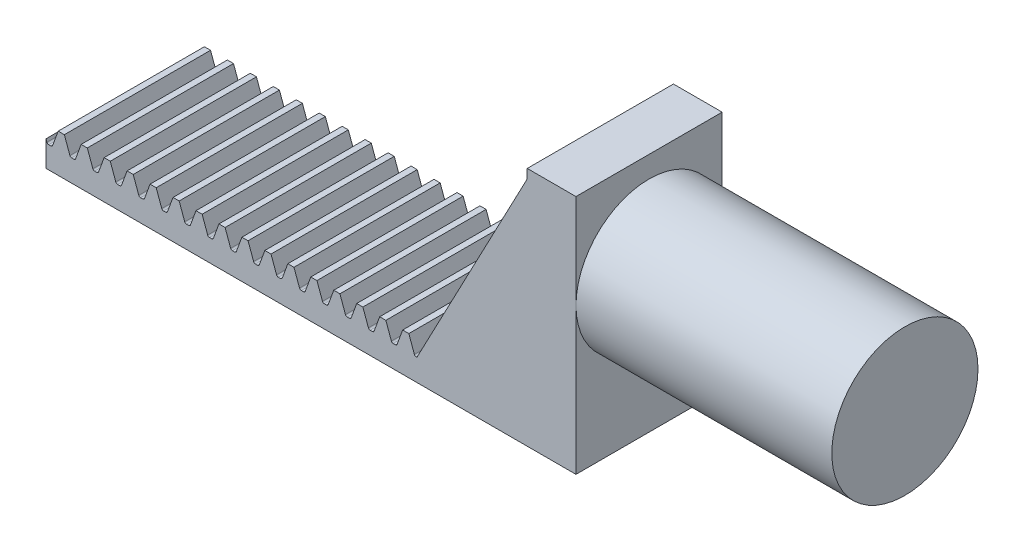
SolidWorks part; units mm, degrees
ref_plane "Front Plane" through (0, 0, 0) normal (0, 0, 1) x (1, 0, 0)
ref_plane "Top Plane" through (0, 0, 0) normal (0, 1, 0) x (1, 0, 0)
ref_plane "Right Plane" through (0, 0, 0) normal (1, 0, 0) x (0, 0, -1)
ref_plane "Plane1" through (0, 0, 19) normal (0, 0, 1) x (1, 0, 0)
sketch "Sketch1" plane through (0, 0, 19) normal (0, 0, 1) x (1, 0, 0)
  line L0 (0, -23.5) -> (0, -29.5)
  line L1 (0, -29.5) -> (131.9469, -29.5)
  line L2 (131.9469, -29.5) -> (131.9469, -23.5)
  line L3 (131.9469, -23.5) -> (131.6361, -23.5)
  line L4 (131.1663, -23.171) -> (129.6482, -19)
  line L5 (129.6482, -19) -> (127.9624, -19)
  line L6 (127.9624, -19) -> (126.4443, -23.171)
  line L7 (125.9745, -23.5) -> (125.3529, -23.5)
  line L8 (124.8831, -23.171) -> (123.365, -19)
  line L9 (123.365, -19) -> (121.6793, -19)
  line L10 (121.6793, -19) -> (120.1611, -23.171)
  line L11 (119.6913, -23.5) -> (119.0698, -23.5)
  line L12 (118.5999, -23.171) -> (117.0818, -19)
  line L13 (117.0818, -19) -> (115.3961, -19)
  line L14 (115.3961, -19) -> (113.8779, -23.171)
  line L15 (113.4081, -23.5) -> (112.7866, -23.5)
  line L16 (112.3167, -23.171) -> (110.7986, -19)
  line L17 (110.7986, -19) -> (109.1129, -19)
  line L18 (109.1129, -19) -> (107.5948, -23.171)
  line L19 (107.1249, -23.5) -> (106.5034, -23.5)
  line L20 (106.0335, -23.171) -> (104.5154, -19)
  line L21 (104.5154, -19) -> (102.8297, -19)
  line L22 (102.8297, -19) -> (101.3116, -23.171)
  line L23 (100.8417, -23.5) -> (100.2202, -23.5)
  line L24 (99.7504, -23.171) -> (98.2322, -19)
  line L25 (98.2322, -19) -> (96.5465, -19)
  line L26 (96.5465, -19) -> (95.0284, -23.171)
  line L27 (94.5585, -23.5) -> (93.937, -23.5)
  line L28 (93.4672, -23.171) -> (91.949, -19)
  line L29 (91.949, -19) -> (90.2633, -19)
  line L30 (90.2633, -19) -> (88.7452, -23.171)
  line L31 (88.2754, -23.5) -> (87.6538, -23.5)
  line L32 (87.184, -23.171) -> (85.6659, -19)
  line L33 (85.6659, -19) -> (83.9801, -19)
  line L34 (83.9801, -19) -> (82.462, -23.171)
  line L35 (81.9922, -23.5) -> (81.3706, -23.5)
  line L36 (80.9008, -23.171) -> (79.3827, -19)
  line L37 (79.3827, -19) -> (77.697, -19)
  line L38 (77.697, -19) -> (76.1788, -23.171)
  line L39 (75.709, -23.5) -> (75.0875, -23.5)
  line L40 (74.6176, -23.171) -> (73.0995, -19)
  line L41 (73.0995, -19) -> (71.4138, -19)
  line L42 (71.4138, -19) -> (69.8957, -23.171)
  line L43 (69.4258, -23.5) -> (68.8043, -23.5)
  line L44 (68.3344, -23.171) -> (66.8163, -19)
  line L45 (66.8163, -19) -> (65.1306, -19)
  line L46 (65.1306, -19) -> (63.6125, -23.171)
  line L47 (63.1426, -23.5) -> (62.5211, -23.5)
  line L48 (62.0512, -23.171) -> (60.5331, -19)
  line L49 (60.5331, -19) -> (58.8474, -19)
  line L50 (58.8474, -19) -> (57.3293, -23.171)
  line L51 (56.8594, -23.5) -> (56.2379, -23.5)
  line L52 (55.7681, -23.171) -> (54.2499, -19)
  line L53 (54.2499, -19) -> (52.5642, -19)
  line L54 (52.5642, -19) -> (51.0461, -23.171)
  line L55 (50.5762, -23.5) -> (49.9547, -23.5)
  line L56 (49.4849, -23.171) -> (47.9667, -19)
  line L57 (47.9667, -19) -> (46.281, -19)
  line L58 (46.281, -19) -> (44.7629, -23.171)
  line L59 (44.2931, -23.5) -> (43.6715, -23.5)
  line L60 (43.2017, -23.171) -> (41.6836, -19)
  line L61 (41.6836, -19) -> (39.9978, -19)
  line L62 (39.9978, -19) -> (38.4797, -23.171)
  line L63 (38.0099, -23.5) -> (37.3883, -23.5)
  line L64 (36.9185, -23.171) -> (35.4004, -19)
  line L65 (35.4004, -19) -> (33.7147, -19)
  line L66 (33.7147, -19) -> (32.1965, -23.171)
  line L67 (31.7267, -23.5) -> (31.1052, -23.5)
  line L68 (30.6353, -23.171) -> (29.1172, -19)
  line L69 (29.1172, -19) -> (27.4315, -19)
  line L70 (27.4315, -19) -> (25.9134, -23.171)
  line L71 (25.4435, -23.5) -> (24.822, -23.5)
  line L72 (24.3521, -23.171) -> (22.834, -19)
  line L73 (22.834, -19) -> (21.1483, -19)
  line L74 (21.1483, -19) -> (19.6302, -23.171)
  line L75 (19.1603, -23.5) -> (18.5388, -23.5)
  line L76 (18.0689, -23.171) -> (16.5508, -19)
  line L77 (16.5508, -19) -> (14.8651, -19)
  line L78 (14.8651, -19) -> (13.347, -23.171)
  line L79 (12.8771, -23.5) -> (12.2556, -23.5)
  line L80 (11.7858, -23.171) -> (10.2676, -19)
  line L81 (10.2676, -19) -> (8.5819, -19)
  line L82 (8.5819, -19) -> (7.0638, -23.171)
  line L83 (6.594, -23.5) -> (5.9724, -23.5)
  line L84 (5.5026, -23.171) -> (3.9844, -19)
  line L85 (3.9844, -19) -> (2.2987, -19)
  line L86 (2.2987, -19) -> (0.7806, -23.171)
  line L87 (0.3108, -23.5) -> (0, -23.5)
  arc A0 (131.6361, -23.5) -> (131.1663, -23.171) centre (131.6361, -23) cw
  arc A1 (126.4443, -23.171) -> (125.9745, -23.5) centre (125.9745, -23) cw
  arc A2 (125.3529, -23.5) -> (124.8831, -23.171) centre (125.3529, -23) cw
  arc A3 (120.1611, -23.171) -> (119.6913, -23.5) centre (119.6913, -23) cw
  arc A4 (119.0698, -23.5) -> (118.5999, -23.171) centre (119.0698, -23) cw
  arc A5 (113.8779, -23.171) -> (113.4081, -23.5) centre (113.4081, -23) cw
  arc A6 (112.7866, -23.5) -> (112.3167, -23.171) centre (112.7866, -23) cw
  arc A7 (107.5948, -23.171) -> (107.1249, -23.5) centre (107.1249, -23) cw
  arc A8 (106.5034, -23.5) -> (106.0335, -23.171) centre (106.5034, -23) cw
  arc A9 (101.3116, -23.171) -> (100.8417, -23.5) centre (100.8417, -23) cw
  arc A10 (100.2202, -23.5) -> (99.7504, -23.171) centre (100.2202, -23) cw
  arc A11 (95.0284, -23.171) -> (94.5585, -23.5) centre (94.5585, -23) cw
  arc A12 (93.937, -23.5) -> (93.4672, -23.171) centre (93.937, -23) cw
  arc A13 (88.7452, -23.171) -> (88.2754, -23.5) centre (88.2754, -23) cw
  arc A14 (87.6538, -23.5) -> (87.184, -23.171) centre (87.6538, -23) cw
  arc A15 (82.462, -23.171) -> (81.9922, -23.5) centre (81.9922, -23) cw
  arc A16 (81.3706, -23.5) -> (80.9008, -23.171) centre (81.3706, -23) cw
  arc A17 (76.1788, -23.171) -> (75.709, -23.5) centre (75.709, -23) cw
  arc A18 (75.0875, -23.5) -> (74.6176, -23.171) centre (75.0875, -23) cw
  arc A19 (69.8957, -23.171) -> (69.4258, -23.5) centre (69.4258, -23) cw
  arc A20 (68.8043, -23.5) -> (68.3344, -23.171) centre (68.8043, -23) cw
  arc A21 (63.6125, -23.171) -> (63.1426, -23.5) centre (63.1426, -23) cw
  arc A22 (62.5211, -23.5) -> (62.0512, -23.171) centre (62.5211, -23) cw
  arc A23 (57.3293, -23.171) -> (56.8594, -23.5) centre (56.8594, -23) cw
  arc A24 (56.2379, -23.5) -> (55.7681, -23.171) centre (56.2379, -23) cw
  arc A25 (51.0461, -23.171) -> (50.5762, -23.5) centre (50.5762, -23) cw
  arc A26 (49.9547, -23.5) -> (49.4849, -23.171) centre (49.9547, -23) cw
  arc A27 (44.7629, -23.171) -> (44.2931, -23.5) centre (44.2931, -23) cw
  arc A28 (43.6715, -23.5) -> (43.2017, -23.171) centre (43.6715, -23) cw
  arc A29 (38.4797, -23.171) -> (38.0099, -23.5) centre (38.0099, -23) cw
  arc A30 (37.3883, -23.5) -> (36.9185, -23.171) centre (37.3883, -23) cw
  arc A31 (32.1965, -23.171) -> (31.7267, -23.5) centre (31.7267, -23) cw
  arc A32 (31.1052, -23.5) -> (30.6353, -23.171) centre (31.1052, -23) cw
  arc A33 (25.9134, -23.171) -> (25.4435, -23.5) centre (25.4435, -23) cw
  arc A34 (24.822, -23.5) -> (24.3521, -23.171) centre (24.822, -23) cw
  arc A35 (19.6302, -23.171) -> (19.1603, -23.5) centre (19.1603, -23) cw
  arc A36 (18.5388, -23.5) -> (18.0689, -23.171) centre (18.5388, -23) cw
  arc A37 (13.347, -23.171) -> (12.8771, -23.5) centre (12.8771, -23) cw
  arc A38 (12.2556, -23.5) -> (11.7858, -23.171) centre (12.2556, -23) cw
  arc A39 (7.0638, -23.171) -> (6.594, -23.5) centre (6.594, -23) cw
  arc A40 (5.9724, -23.5) -> (5.5026, -23.171) centre (5.9724, -23) cw
  arc A41 (0.7806, -23.171) -> (0.3108, -23.5) centre (0.3108, -23) cw
  point P172 (0, 0)
  point P174 (0, 0)
extrude "Boss-Extrude1" add sketch "Sketch1" against normal mid plane 40 from offset 0
scale "Scale1" scale about centroid uniform scaling yes scale factor 0.3
sketch "Sketch8" plane through (0, 0, 25) normal (0, 0, 1) x (1, 0, 0)
  line L0 (82.9123, -26.4286) -> (92.9123, -26.4286)
  line L2 (92.9123, -26.4286) -> (92.9123, -7.4286)
  line L3 (92.9123, -7.4286) -> (82.9123, -26.4286)
  line L4 (46.1814, -26.4286) -> (85.7655, -26.4286) construction
  point P4 (0, 0)
  dimension "D1" = 10
  dimension "D2" = 19
extrude "Boss-Extrude5" add sketch "Sketch8" against normal up to surface (12 mm away) up to face at (65.9734, -24.1955, 13)
sketch "Sketch4" plane through (92.9123, 0, 0) normal (1, 0, 0) x (0, 0, -1)
  line L0 (-13, -26.4286) -> (-13, -7.4286) construction
  line L2 (-13, -26.4286) -> (-13, -14.4286)
  line L3 (-13, -14.4286) -> (-25, -14.4286) construction
  line L4 (-25, -26.4286) -> (-25, -14.4286)
  line L6 (-13, -26.4286) -> (-25, -26.4286)
  line L7 (-13, -14.4286) -> (-25, -14.4286) construction
  line L8 (-13, -14.4286) -> (-13, -6.6786)
  line L9 (-13, -6.6786) -> (-25, -6.6786)
  line L10 (-25, -14.4286) -> (-25, -6.6786)
  line L11 (-13, -26.4286) -> (-25, -26.4286) construction
  point P6 (-19, -26.4286)
  point P11 (-5.207, -26.4286)
  point P12 (-19, -26.4286)
  dimension "D1" = 12
  dimension "D2" = 7.75
extrude "Boss-Extrude2" add sketch "Sketch4" along normal blind 4
sketch "Sketch5" plane through (96.9123, 0, 0) normal (1, 0, 0) x (0, 0, -1)
  line L0 (-13, -14.4286) -> (-25, -14.4286) construction
  circle A0 centre (-19, -14.4286) radius 6
  dimension "D1" = 12
extrude "Boss-Extrude3" add sketch "Sketch5" along normal blind 21
sketch "Sketch6" [suppressed] plane through (0, 0, 25) normal (0, 0, 1) x (1, 0, 0)
  line L0 (92.9123, -6.6786) -> (77.9123, -26.4286)
  line L1 (46.1814, -26.4286) -> (92.9123, -26.4286) construction
  line L2 (92.9123, -26.4286) -> (77.9123, -26.4286)
  line L3 (92.9123, -26.4286) -> (92.9123, -6.6786)
  dimension "D1" = 15
ref_plane "Plane2" through (46.1814, -26.4286, 25) normal (1, 0, 0) x (0, 0, -1)
sketch "Sketch10" plane through (0, 0, 25) normal (0, 0, 1) x (1, 0, 0)
  line L0 (51.1467, -23.2786) -> (50.6409, -23.2786) construction
  line L1 (46.1814, -26.4286) -> (53.4114, -26.4286)
  line L2 (46.1814, -26.4286) -> (46.1814, -23.2786)
  line L3 (46.1814, -23.2786) -> (53.4114, -23.2786)
  line L4 (53.4114, -26.4286) -> (53.4114, -23.2786)
  dimension "D1" = 7.23
extrude "Cut-Extrude1" cut sketch "Sketch10" against normal up to surface (12 mm away) up to face at (66.0664, -23.7165, 13)
